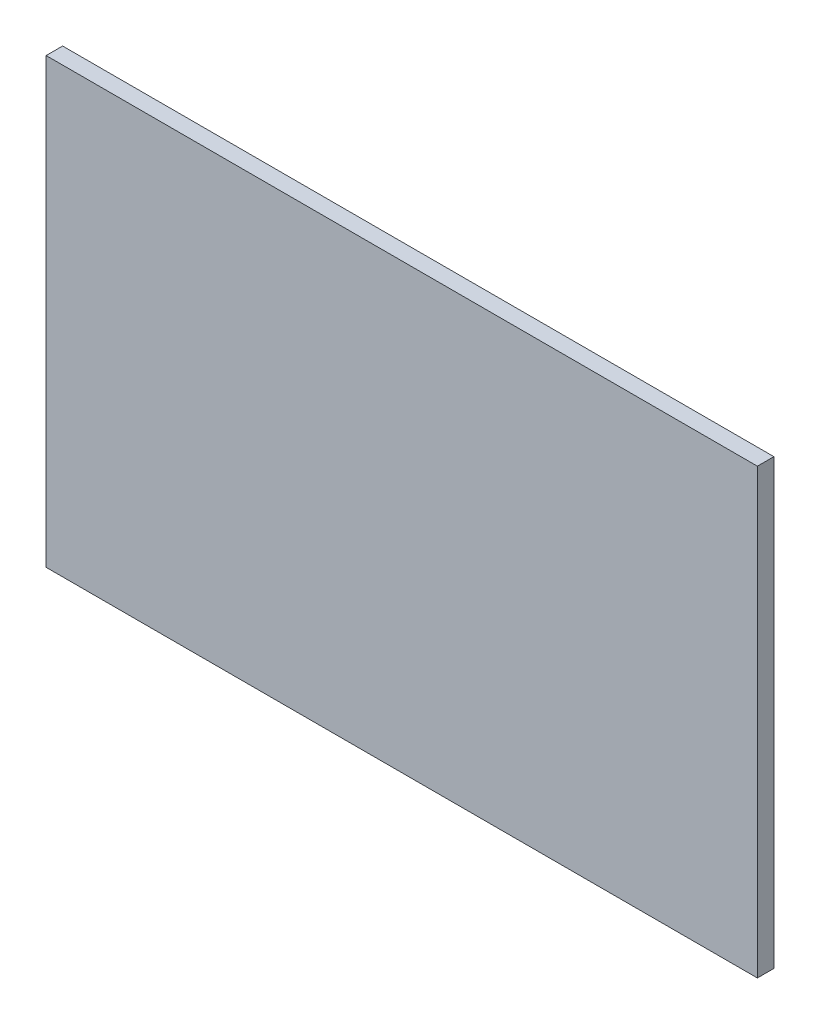
SolidWorks part; units mm, degrees
ref_plane "Front Plane" through (0, 0, 0) normal (0, 0, 1) x (1, 0, 0)
ref_plane "Top Plane" through (0, 0, 0) normal (0, 1, 0) x (1, 0, 0)
ref_plane "Right Plane" through (0, 0, 0) normal (1, 0, 0) x (0, 0, -1)
sketch "Sketch1" plane through (0, 0, 0) normal (0, 0, 1) x (1, 0, 0)
  line L1 (-69, -43) -> (69, -43)
  line L2 (-69, -43) -> (-69, 43)
  line L3 (-69, 43) -> (69, 43)
  line L4 (69, -43) -> (69, 43)
  line L5 (-69, -43) -> (69, 43) construction
  line L6 (-69, 43) -> (69, -43) construction
  point P0 (0, 0)
  dimension "D1" = 86
  dimension "D2" = 138
extrude "Boss-Extrude1" add sketch "Sketch1" along normal blind 3.2
